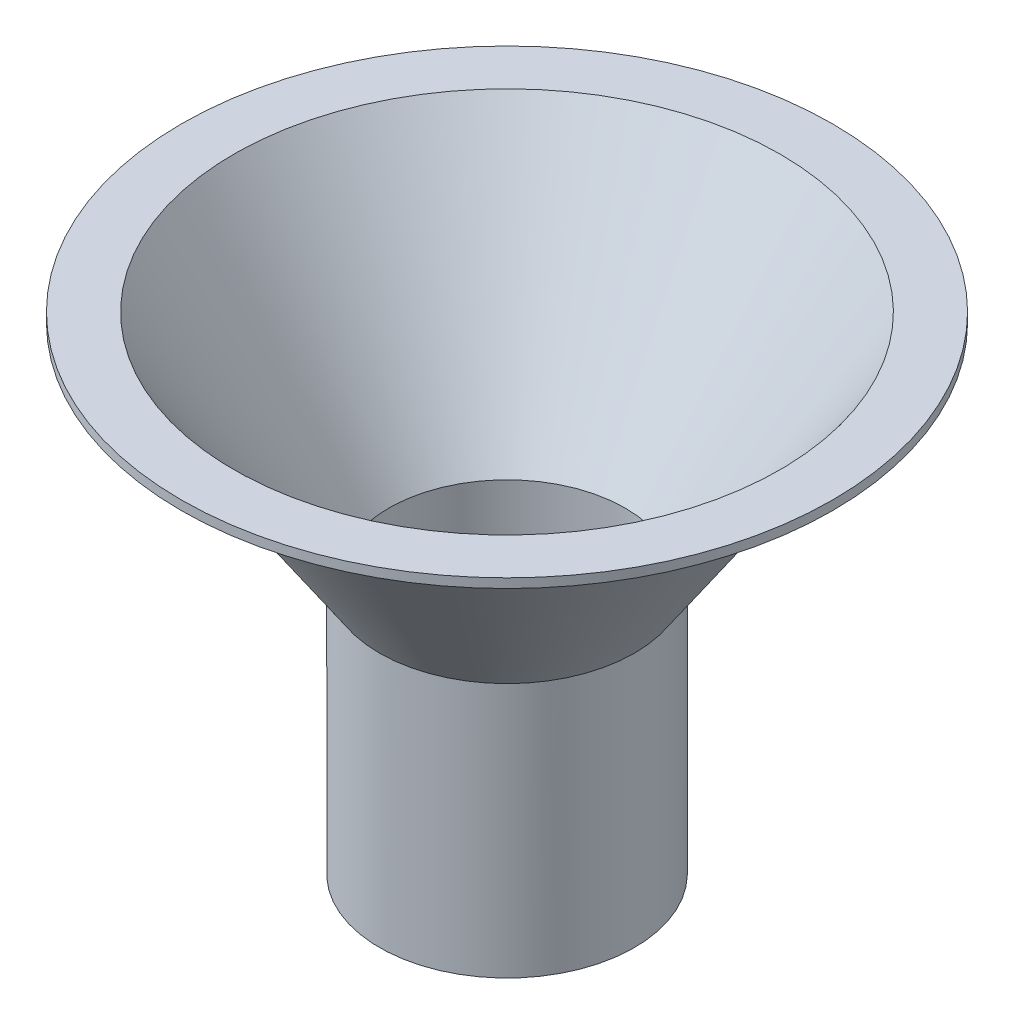
SolidWorks part; units mm, degrees
ref_plane "Front Plane" through (0, 0, 0) normal (0, 0, 1) x (1, 0, 0)
ref_plane "Top Plane" through (0, 0, 0) normal (0, 1, 0) x (1, 0, 0)
ref_plane "Right Plane" through (0, 0, 0) normal (1, 0, 0) x (0, 0, -1)
sketch "Sketch1" plane through (0, 0, 0) normal (0, 0, 1) x (1, 0, 0)
  line L0 (0, 0) -> (0, 42) construction
  line L1 (0, 0) -> (-29, 0) construction
  line L2 (-29, 0) -> (-29, 42) construction
  line L3 (-29, 42) -> (0, 42) construction
  line L4 (-29, 0) -> (-29, 0.8) construction
  line L6 (-11, 20) -> (-11, 42) construction
  line L7 (-11, 42) -> (-10.2, 42) construction
  line L11 (-29, 0) -> (-23.5755, 0) construction
  line L12 (-29, 0.8) -> (-24, 0.8) construction
  line L13 (-24, 0.8) -> (-11, 20) construction
  line L14 (-10.2, 19.7546) -> (-23.5755, 0) construction
  line L15 (0, 0) -> (0, -1) construction
  line L16 (0, -1) -> (-29, -1) construction
  line L17 (-10.2, 19.7546) -> (-10.2, 42) construction
  line L18 (-29, -1) -> (-29, 0) construction
  line L19 (-29, -2) -> (-23.5755, -2) construction
  line L20 (-10.2, -21.7546) -> (-23.5755, -2) construction
  line L21 (-10.2, -21.7546) -> (-10.2, -44) construction
  line L22 (-11, -44) -> (-10.2, -44) construction
  line L23 (-11, -22) -> (-11, -44) construction
  line L24 (-24, -2.8) -> (-11, -22) construction
  line L25 (-29, -2.8) -> (-24, -2.8) construction
  line L26 (-29, -2) -> (-29, -2.8) construction
  line L27 (-28, 0.8) -> (-28, 1.8) construction
  line L28 (-28, 1.8) -> (-21.2917, 4.8) construction
  line L29 (-21.2917, 4.8) -> (-24, 0.8) construction
  line L30 (-24, 0.8) -> (-28, 0.8) construction
  line L31 (-21.2917, -6.8) -> (-24, -2.8) construction
  line L32 (-28, -3.8) -> (-21.2917, -6.8) construction
  line L33 (-28, -2.8) -> (-28, -3.8) construction
  line L34 (-24, -2.8) -> (-28, -2.8) construction
  dimension "D10" = 0.8
  dimension "D11" = 1
  dimension "D14" = 55.899
  dimension "D2" = 29
  dimension "D3" = 0.8
  dimension "D4" = 42
  dimension "D5" = 22
  dimension "D6" = 11
  dimension "D7" = 1
  dimension "D8" = 1
  dimension "D9" = 5
  dimension "D12" = 4
sketch "Sketch2" plane through (0, 0, 0) normal (0, 0, 1) x (1, 0, 0)
  line L0 (-28, 1.8) -> (-21.2917, 4.8) construction
  line L1 (-28, 0.8) -> (-28, 1.8) construction
  line L2 (-29, 0.8) -> (-24, 0.8) construction
  line L3 (-10.2, 19.7546) -> (-23.5755, 0) construction
  line L4 (-24, 0.8) -> (-11, 20) construction
  line L5 (-10.2, 19.7546) -> (-10.2, 42) construction
  line L6 (-11, 20) -> (-11, 42) construction
  line L7 (-28, 1.8) -> (-21.2917, 4.8)
  line L8 (-28, 0.8) -> (-28, 1.8)
  line L9 (-29, 0.8) -> (-28, 0.8)
  line L10 (-10.2, 19.7546) -> (-23.5755, 0)
  line L11 (-21.2917, 4.8) -> (-11, 20)
  line L12 (-10.2, 19.7546) -> (-10.2, 42)
  line L13 (-11, 20) -> (-11, 42)
  line L14 (-29, 0.8) -> (-29, 0)
  line L15 (-29, 0) -> (-23.5755, 0)
  line L16 (-11, 42) -> (-10.2, 42)
sketch "Sketch3" plane through (0, 0, 0) normal (0, 0, 1) x (1, 0, 0)
  line L0 (-11, -44) -> (-10.2, -44) construction
  line L1 (-10.2, -21.7546) -> (-10.2, -44) construction
  line L2 (-11, -22) -> (-11, -44) construction
  line L3 (-10.2, -21.7546) -> (-23.5755, -2) construction
  line L4 (-24, -2.8) -> (-11, -22) construction
  line L5 (-28, -3.8) -> (-21.2917, -6.8) construction
  line L6 (-28, -2.8) -> (-28, -3.8) construction
  line L7 (-29, -2.8) -> (-24, -2.8) construction
  line L8 (-29, -2) -> (-29, -2.8) construction
  line L9 (-29, -2) -> (-23.5755, -2) construction
  line L10 (-11, -44) -> (-10.2, -44)
  line L11 (-10.2, -21.7546) -> (-10.2, -44)
  line L12 (-11, -22) -> (-11, -44)
  line L13 (-10.2, -21.7546) -> (-23.5755, -2)
  line L14 (-21.2917, -6.8) -> (-11, -22)
  line L15 (-28, -3.8) -> (-21.2917, -6.8)
  line L16 (-28, -2.8) -> (-28, -3.8)
  line L17 (-29, -2.8) -> (-28, -2.8)
  line L18 (-29, -2) -> (-29, -2.8)
  line L19 (-29, -2) -> (-23.5755, -2)
revolve "Revolve3" add sketch "Sketch3" angle 360 about L0
sketch "Sketch4" plane through (0, 0, 0) normal (0, 0, 1) x (1, 0, 0)
  line L0 (-29, -2.8) -> (-29, -2)
  line L1 (-29, -2) -> (-28.1, -2)
  line L2 (-29, -2) -> (-29, -2.8)
  line L3 (-29, -2.8) -> (-28.1, -2.8)
  line L4 (-28.1, -2) -> (-28.1, -2.8)
  line L5 (29, -2) -> (29, -2.8)
  line L6 (29, -2) -> (29, -2.8) construction
  line L7 (-29, -2.8) -> (-29, -2) construction
  line L8 (-28, -3.8) -> (-28, -2.8)
  line L9 (28, -2.8) -> (28, -3.8)
  line L10 (28, -2.8) -> (28, -3.8) construction
  line L11 (-28, -3.8) -> (-28, -2.8) construction
  line L12 (0, 0) -> (0, -44) construction
  line L13 (-11, -44) -> (11, -44) construction
  dimension "D1" = 0.2
revolve "Cut-Revolve1" cut sketch "Sketch4" angle 360 about L12
sketch "Sketch5" plane through (0, 0, 0) normal (0, 0, 1) x (1, 0, 0)
  line L0 (28, -3.8) -> (21.2917, -6.8)
  line L1 (-21.2917, -6.8) -> (-28, -3.8)
  line L2 (-21.2917, -6.8) -> (-28, -3.8)
  line L3 (28, -3.8) -> (21.2917, -6.8)
  line L4 (-28, -3.8) -> (-28, -2.8)
  line L5 (28, -2.8) -> (28, -3.8)
  line L6 (28, -2.8) -> (28, -3.8)
  line L7 (-28, -3.8) -> (-28, -2.8)
  line L8 (-28, -2.8) -> (-21.2917, -6.8)
  line L9 (0, 0) -> (0, -44) construction
  line L10 (-10.2, -44) -> (10.2, -44) construction
revolve "Cut-Revolve2" cut sketch "Sketch5" angle 360 about L9
